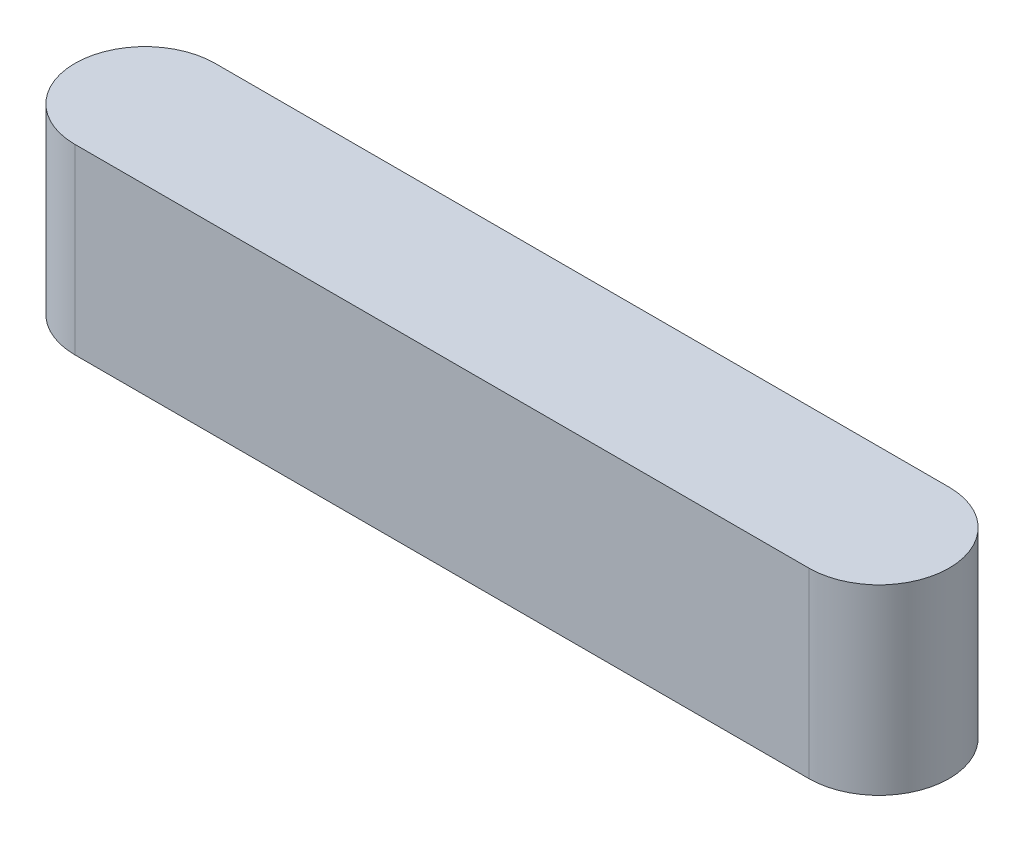
SolidWorks part; units mm, degrees
ref_plane "Front Plane" through (0, 0, 0) normal (0, 0, 1) x (1, 0, 0)
ref_plane "Top Plane" through (0, 0, 0) normal (0, 1, 0) x (1, 0, 0)
ref_plane "Right Plane" through (0, 0, 0) normal (1, 0, 0) x (0, 0, -1)
sketch "Sketch1" plane through (0, 0, 0) normal (0, 1, 0) x (1, 0, 0)
  line L0 (0, 0) -> (31.4, 0) construction
  line L1 (0, 3) -> (31.4, 3)
  line L2 (0, -3) -> (31.4, -3)
  arc A0 (0, 3) -> (0, -3) centre (0, 0) ccw
  arc A1 (31.4, -3) -> (31.4, 3) centre (31.4, 0) ccw
  point P3 (15.7, 0)
  point P8 (-3, 0)
  point P9 (34.4, 0)
  dimension "D1" = 6
  dimension "D2" = 37.4
extrude "Boss-Extrude1" add sketch "Sketch1" along normal blind 7.8
